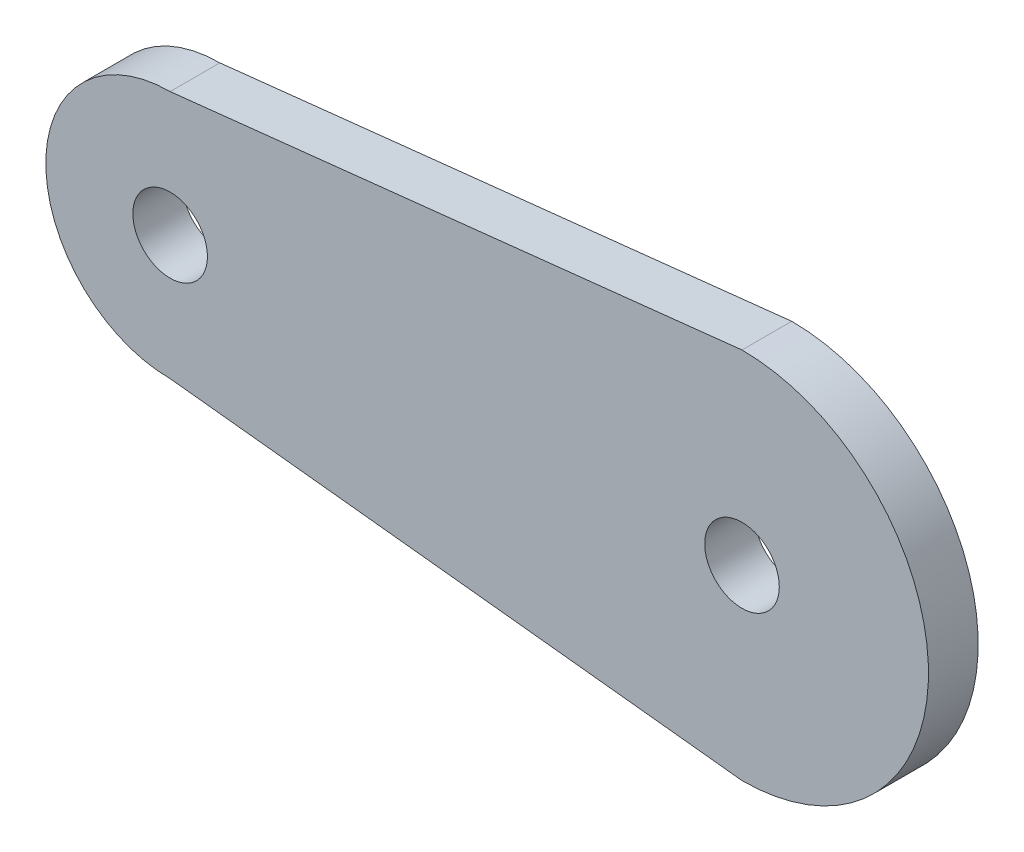
SolidWorks part; units mm, degrees
ref_plane "Front Plane" through (0, 0, 0) normal (0, 0, 1) x (1, 0, 0)
ref_plane "Top Plane" through (0, 0, 0) normal (0, 1, 0) x (1, 0, 0)
ref_plane "Right Plane" through (0, 0, 0) normal (1, 0, 0) x (0, 0, -1)
sketch "Sketch1" plane through (0, 0, 0) normal (0, 0, 1) x (1, 0, 0)
  line L0 (0, 0) -> (23, 0) construction
  line L1 (0, 5) -> (0, -5) construction
  line L2 (23, 7.5) -> (23, -7.5) construction
  line L3 (0, 5) -> (23, 7.5)
  line L4 (0, -5) -> (23, -7.5)
  circle A0 centre (0, 0) radius 1.5
  circle A1 centre (23, 0) radius 1.5
  arc A2 (0, 5) -> (0, -5) centre (0, 0) ccw
  arc A3 (23, 7.5) -> (23, -7.5) centre (23, 0) cw
  dimension "D5" = 5
  dimension "D6" = 3
  dimension "D7" = 3
  dimension "D1" = 23
  dimension "D2" = 10
  dimension "D3" = 15
  dimension "D4" = 7.5
extrude "Boss-Extrude1" add sketch "Sketch1" along normal blind 16 contours A3 L3 A2 L4 A1 A0
ref_plane "Plane1" through (0, 7.5, 0) normal (0, 1, 0) x (1, 0, 0)
sketch "Sketch3" plane through (0, 7.5, 0) normal (0, 1, 0) x (1, 0, 0)
  line L1 (41.5858, -2) -> (-6.9747, -2)
  line L2 (41.5858, -2) -> (41.5858, -14)
  line L3 (41.5858, -14) -> (-6.9747, -14)
  line L4 (-6.9747, -2) -> (-6.9747, -14)
  line L5 (-1.5, -16) -> (1.5, -16) construction
  dimension "D1" = 12
  dimension "D2" = 2
extrude "Cut-Extrude1" cut sketch "Sketch3" against normal through all
sketch "Sketch4" plane through (0, 0, 0) normal (0, 0, -1) x (-1, 0, 0)
  line L1 (8.1643, -9.1352) -> (-32.5472, -9.1352)
  line L2 (8.1643, -9.1352) -> (8.1643, 15.7343)
  line L3 (8.1643, 15.7343) -> (-32.5472, 15.7343)
  line L4 (-32.5472, -9.1352) -> (-32.5472, 15.7343)
extrude "Cut-Extrude2" cut sketch "Sketch4" against normal blind 10
